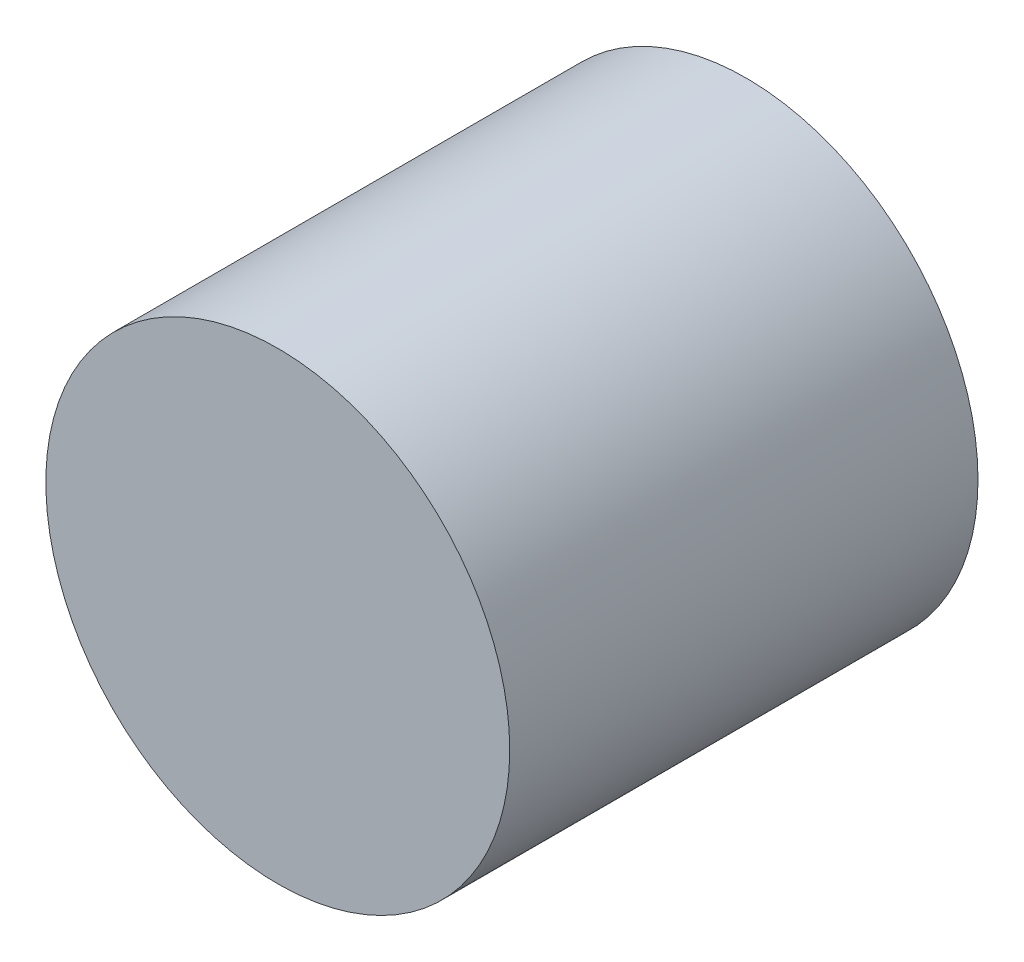
SolidWorks part; units mm, degrees
ref_plane "Front Plane" through (0, 0, 0) normal (0, 0, 1) x (1, 0, 0)
ref_plane "Top Plane" through (0, 0, 0) normal (0, 1, 0) x (1, 0, 0)
ref_plane "Right Plane" through (0, 0, 0) normal (1, 0, 0) x (0, 0, -1)
sketch "Sketch1" plane through (0, 0, 0) normal (0, 0, 1) x (1, 0, 0)
  circle A0 centre (0, 0) radius 7.925
  dimension "D1" = 15.85
extrude "Boss-Extrude1" add sketch "Sketch1" along normal blind 16
